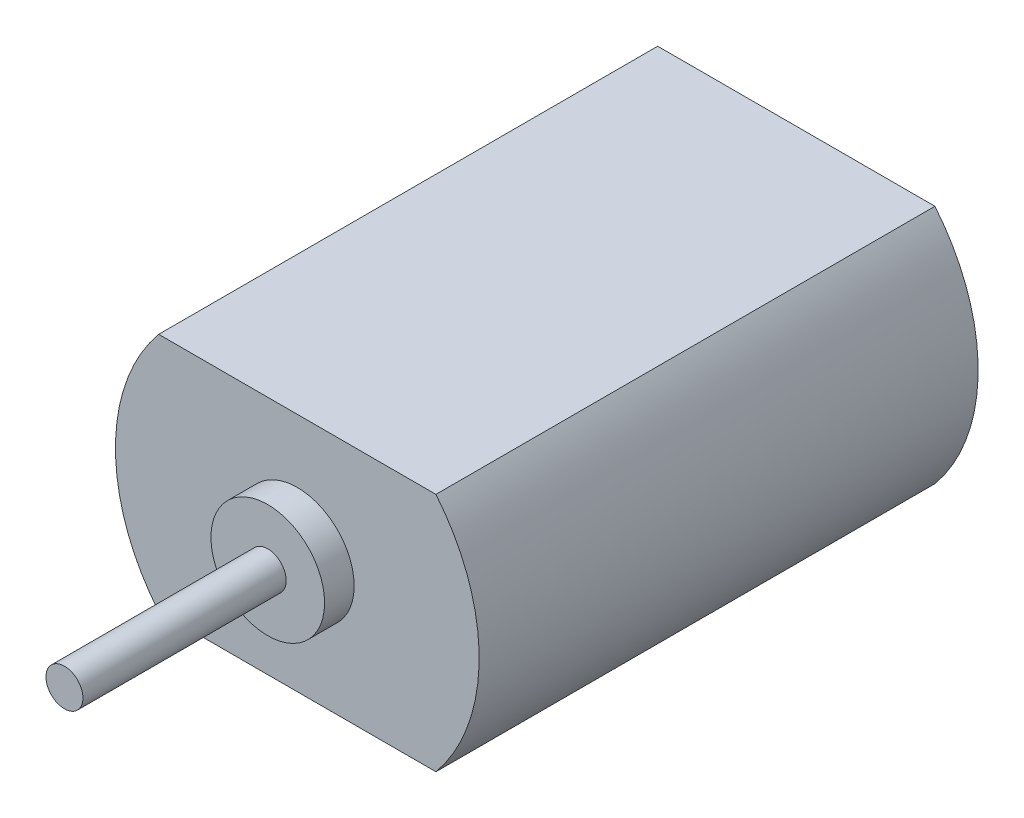
SolidWorks part; units mm, degrees
ref_plane "Front Plane" through (0, 0, 0) normal (0, 0, 1) x (1, 0, 0)
ref_plane "Top Plane" through (0, 0, 0) normal (0, 1, 0) x (1, 0, 0)
ref_plane "Right Plane" through (0, 0, 0) normal (1, 0, 0) x (0, 0, -1)
sketch "Sketch1" plane through (0, 0, 0) normal (0, 0, 1) x (1, 0, 0)
  line L0 (0, 0) -> (0, 6.5) construction
  line L1 (-7.5, -6.5) -> (7.5, -6.5)
  line L2 (-7.5, -6.5) -> (-7.5, 6.5)
  line L3 (-7.5, 6.5) -> (7.5, 6.5)
  line L4 (7.5, -6.5) -> (7.5, 6.5)
  line L5 (-7.5, -6.5) -> (7.5, 6.5) construction
  line L6 (-7.5, 6.5) -> (7.5, -6.5) construction
  arc A0 (7.5, 6.5) -> (7.5, -6.5) centre (-0.3607, 0) cw
  arc A1 (-7.5, 6.5) -> (-7.5, -6.5) centre (0.3607, 0) ccw
  point P0 (0, 0)
  dimension "D1" = 15
  dimension "D2" = 13
extrude "Boss-Extrude1" add sketch "Sketch1" along normal blind 27 contours L1 L4 L3 L2 | A0 L4 | L2 A1
sketch "Sketch2" plane through (0, 0, 27) normal (0, 0, 1) x (1, 0, 0)
  circle A0 centre (0, 0) radius 3.075
extrude "Boss-Extrude2" add sketch "Sketch2" along normal blind 1.6
sketch "Sketch3" plane through (0, 0, 28.6) normal (0, 0, 1) x (1, 0, 0)
  circle A0 centre (0, 0) radius 1
extrude "Boss-Extrude3" add sketch "Sketch3" along normal blind 11
